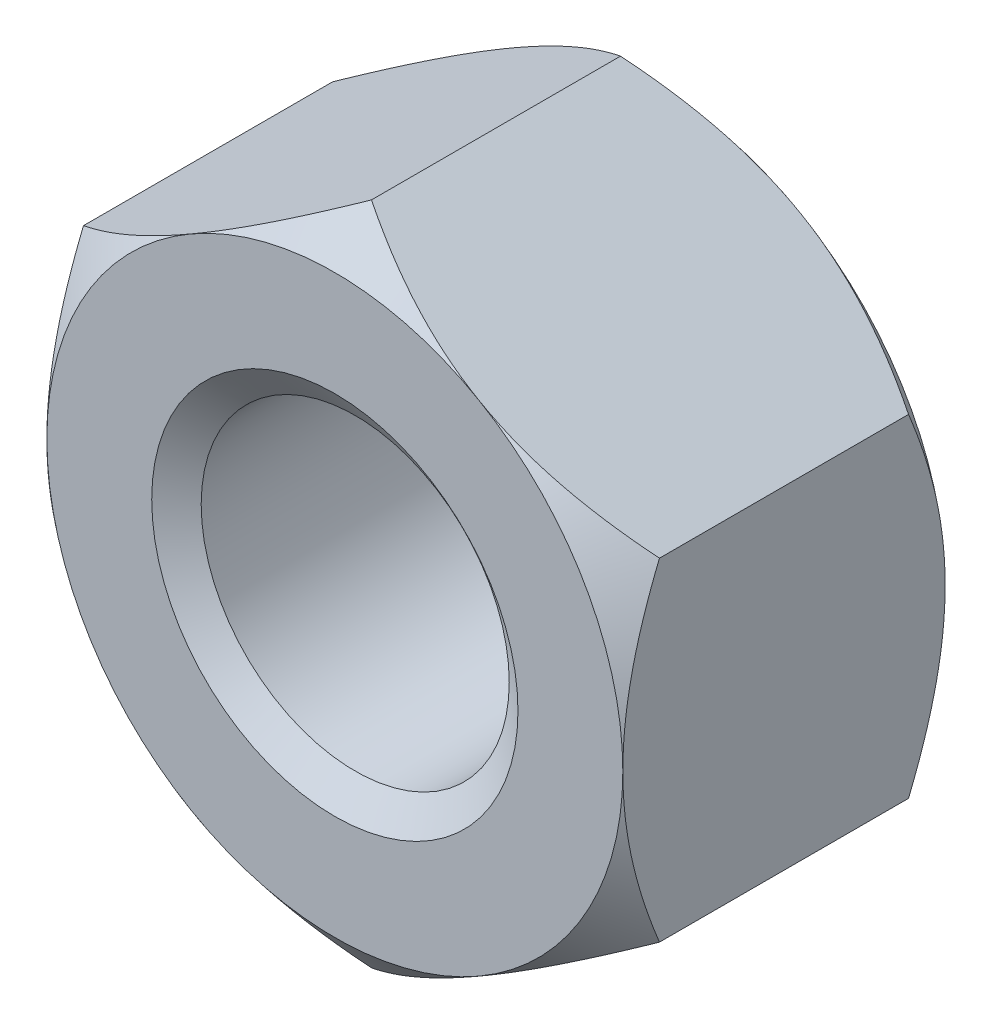
SolidWorks part; units mm, degrees
extrude "BaseNut" add sketch "BaseNutSke" against normal blind 9.779
sketch "BaseNutSke" plane through (0, 0, 0) normal (0, 0, 1) x (1, 0, 0)
  line L6 (8.7376, 5.0447) -> (8.7376, -5.0447)
  line L7 (-8.7376, 5.0447) -> (-8.7376, -5.0447)
  line L8 (8.7376, 5.0447) -> (0, 10.0893)
  line L9 (0, 10.0893) -> (-8.7376, 5.0447)
  line L10 (-8.7376, -5.0447) -> (0, -10.0893)
  line L11 (0, -10.0893) -> (8.7376, -5.0447)
  circle A0 centre (0, 0) radius 4.6736
  dimension "Tap_drill" = 9.3472
  dimension "Width_flats" = 17.4752
  dimension "D2" = 8.7376
  dimension "D3" = 8.7376
  dimension "D1" = 120
  dimension "D4" = 8.7376
cosmetic thread "ThreadCosmetic" parameters "Thread_major"=11.1125
pattern_linear "ThdSchPat" [suppressed]
revolve "ThreadSchematic" [suppressed] cut sketch "ThdSchSke" angle 360 about L6
sketch "ThdSchSke" plane through (0, 0, 0) normal (0, 1, 0) x (1, 0, 0)
  line L0 (-5.5562, 0.0254) -> (-4.6736, 0.6434)
  line L1 (-4.6736, 0.6434) -> (-2.3368, 0.6434)
  line L2 (-2.3368, 0.6434) -> (-2.3368, -0.5926)
  line L3 (-2.3368, -0.5926) -> (-4.6736, -0.5926)
  line L4 (-4.6736, -0.5926) -> (-5.5562, 0.0254)
  line L5 (-3.175, 1.8136) -> (3.175, 1.8136) construction
  line L6 (0, 1.8136) -> (0, -2.9874) construction
  line L7 (0, 9.1356) -> (0, 0.618) construction
  dimension "Thread_major" = 11.1125
  dimension "SideAngle" = 55
  dimension "Advance" = 1.8136
  dimension "D1" = 0.0254
ref_plane "Plane1" through (0, 0, 0) normal (0, 0, 1) x (1, 0, 0)
ref_plane "Plane2" through (0, 0, 0) normal (0, 1, 0) x (1, 0, 0)
ref_plane "Plane3" through (0, 0, 0) normal (1, 0, 0) x (0, 0, -1)
other "Configuration Table"
sketch "Sketch4" plane through (0, 0, 0) normal (1, 0, 0) x (0, 0, -1)
  line L0 (9.779, 8.7376) -> (9.3726, 8.7376)
  line L1 (9.779, 8.7376) -> (9.779, 22.7893)
  line L2 (9.3726, 22.7893) -> (9.779, 22.7893)
  line L3 (9.3726, 22.7893) -> (9.3726, 8.7376)
  line L4 (0, 0) -> (34.925, 0) construction
  line L6 (9.779, 5.0447) -> (9.779, 10.0893) construction
  line L7 (0, 8.7376) -> (-12.7, 8.7376)
  line L8 (0, 5.0447) -> (0, 10.0893) construction
  line L9 (1.1112, 10.0893) -> (1.1113, 22.7893)
  line L10 (1.1113, 22.7893) -> (-12.7, 22.7893)
  line L11 (-12.7, 22.7893) -> (-12.7, 8.7376)
  line L12 (0, 8.7376) -> (1.1112, 10.0893)
  line L14 (0, 5.0447) -> (0, -5.0447) construction
  line L15 (9.779, 10.0893) -> (0, 10.0893) construction
  dimension "D1" = 8.7376
  dimension "D2" = 1.1113
  dimension "D3" = 12.7
  dimension "D4" = 12.7
revolve "Bearing-Face" [suppressed] cut sketch "Sketch4" angle 360 about L4
sketch "Sketch3" plane through (0, 0, 0) normal (1, 0, 0) x (0, 0, -1)
  line L0 (9.779, 8.7376) -> (8.6677, 10.0893)
  line L1 (8.6677, 10.0893) -> (8.6677, 22.7893)
  line L2 (8.6677, 22.7893) -> (22.479, 22.7893)
  line L3 (22.479, 22.7893) -> (22.479, 8.7376)
  line L4 (22.479, 8.7376) -> (9.779, 8.7376)
  line L5 (9.779, 5.0447) -> (9.779, 10.0893) construction
  line L6 (9.779, 10.0893) -> (0, 10.0893) construction
  line L7 (0, 0) -> (38.6776, 0) construction
  line L8 (9.779, 0) -> (0, 0) construction
  line L9 (4.8895, 10.0893) -> (4.8895, 44.222) construction
  line L10 (1.1112, 22.7893) -> (-12.7, 22.7893)
  line L11 (-12.7, 22.7893) -> (-12.7, 8.7376)
  line L12 (-12.7, 8.7376) -> (0, 8.7376)
  line L13 (0, 8.7376) -> (1.1112, 10.0893)
  line L14 (1.1112, 10.0893) -> (1.1112, 22.7893)
  line L16 (9.779, 10.0893) -> (0, 10.0893) construction
  dimension "D1" = 8.7376
  dimension "D2" = 1.1113
  dimension "D4" = 12.7
  dimension "D3" = 12.7
revolve "Double-Chamfer" cut sketch "Sketch3" angle 360 about L7
sketch "Sketch5" plane through (0, 0, 0) normal (1, 0, 0) x (0, 0, -1)
  line L0 (9.7536, 5.5562) -> (9.0738, 4.5853)
  line L1 (9.8044, 5.5563) -> (9.7536, 5.5562)
  line L2 (9.8044, 5.5563) -> (9.8044, 4.5853)
  line L3 (9.8044, 4.5853) -> (9.0738, 4.5853)
  line L6 (-0.0508, 5.5562) -> (0, 5.5562)
  line L7 (0, 5.5562) -> (0.6798, 4.5853)
  line L9 (0.6798, 4.5853) -> (-0.0508, 4.5853)
  line L10 (-0.0508, 4.5853) -> (-0.0508, 5.5562)
  line L11 (25.0375, 0) -> (38.388, 0) construction
  line L12 (9.779, 0) -> (0, 0) construction
  dimension "D1" = 35
  dimension "D2" = 0.0508
  dimension "ThreadMajor" = 5.5562
  dimension "Offset1" = 9.8044
revolve "EndChamfer" cut sketch "Sketch5" angle 360 about L11
equation "\"D2@BaseNutSke\" = \"Width_flats@BaseNutSke\" / 2"
equation "\"D3@BaseNutSke\" = \"Width_flats@BaseNutSke\" / 2"
equation "\"D1@Sketch3\" = \"Width_flats@BaseNutSke\" /2"
equation "\"D2@Sketch3\" = \"Thread_major@ThreadCosmetic\" *.1"
equation "\"D1@Sketch4\" = \"D2@BaseNutSke\""
equation "\"D2@Sketch4\" = \"Thread_major@ThreadCosmetic\" *.10"
equation "\"D4@BaseNutSke\" = \"D3@BaseNutSke\""
equation "\"Thread_major@ThdSchSke\" = \"Thread_major@ThreadCosmetic\""
equation "\"Tap_Drill@ThdSchSke\" = \"Tap_drill@BaseNutSke\""
equation "\"OverCut@ThdSchSke\" = \"Tap_Drill@ThdSchSke\" * 0.5"
equation "\"Num_threads@ThdSchPat\" = int(  ( \"Thickness@BaseNut\" - 0.002 ) / \"Advance@ThdSchSke\" + 0.999 )  + 1"
equation "\"Advance@ThdSchPat\" = ( \"Thickness@BaseNut\" - 0.002 ) /  (\"Num_threads@ThdSchPat\" - 1) 'relax it"
equation "' \"Num_threads@ThdSchPat\" = \"Num_threads@ThdSchPat\" - sgn( \"Num_threads@ThdSchPat\" - 1) '---chamfered tips only---"
equation "\"ThreadMajor@Sketch5\" = \"Thread_major@ThreadCosmetic\" * 0.5"
equation "\"ChamferDepth@Sketch5\" = (\"Thread_major@ThreadCosmetic\" - \"Tap_drill@BaseNutSke\") * 0.55"
equation "\"Offset1@Sketch5\" = \"Thickness@BaseNut\" + 0.001"
equation "\"Offset2@Sketch5\" = \"Offset1@Sketch5\" + 0.002"
